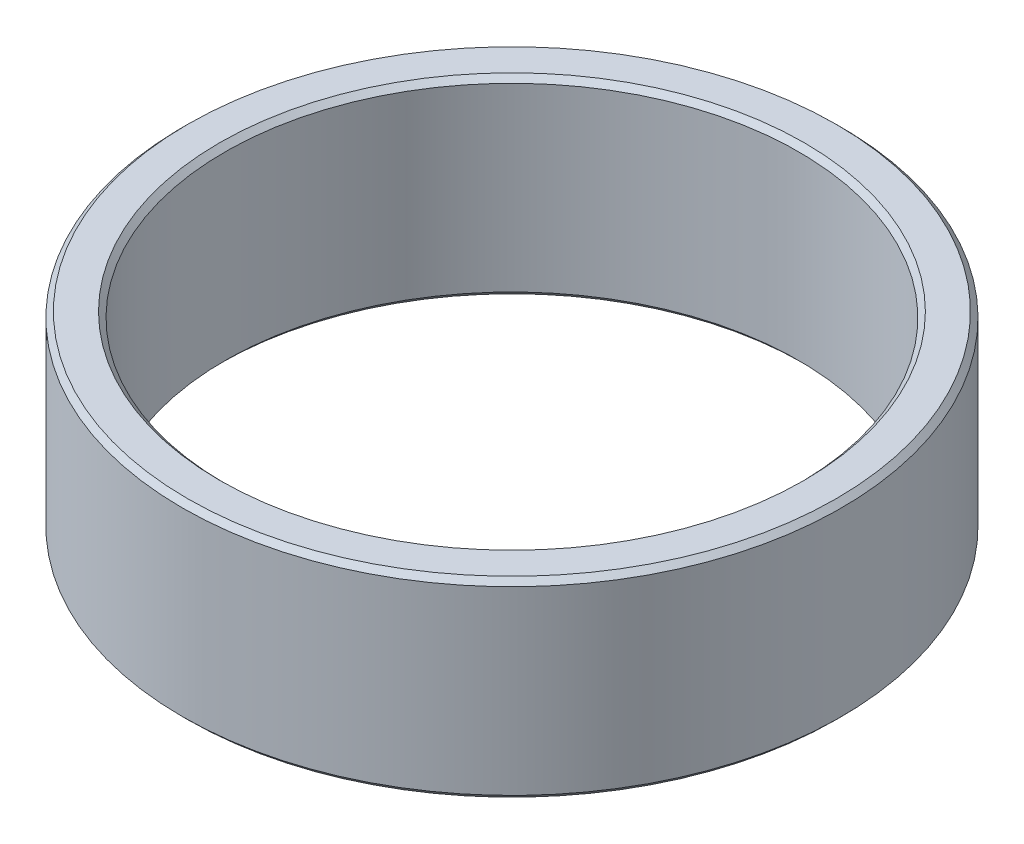
SolidWorks part; units mm, degrees
ref_plane "Piano frontale" through (0, 0, 0) normal (0, 0, 1) x (1, 0, 0)
ref_plane "Piano superiore" through (0, 0, 0) normal (0, 1, 0) x (1, 0, 0)
ref_plane "Piano destro" through (0, 0, 0) normal (1, 0, 0) x (0, 0, -1)
sketch "Schizzo1" plane through (0, 0, 0) normal (0, 1, 0) x (1, 0, 0)
  circle A0 centre (0, 0) radius 31
  circle A1 centre (0, 0) radius 27
  dimension "D1" = 62
  dimension "D2" = 54
extrude "Estrusione1" add sketch "Schizzo1" along normal blind 18
chamfer "Smusso1" distance 0.5 angle 45 4 edges at (0, 0, 27) (0, 0, 31) (0, 18, 27) (0, 18, 31)
